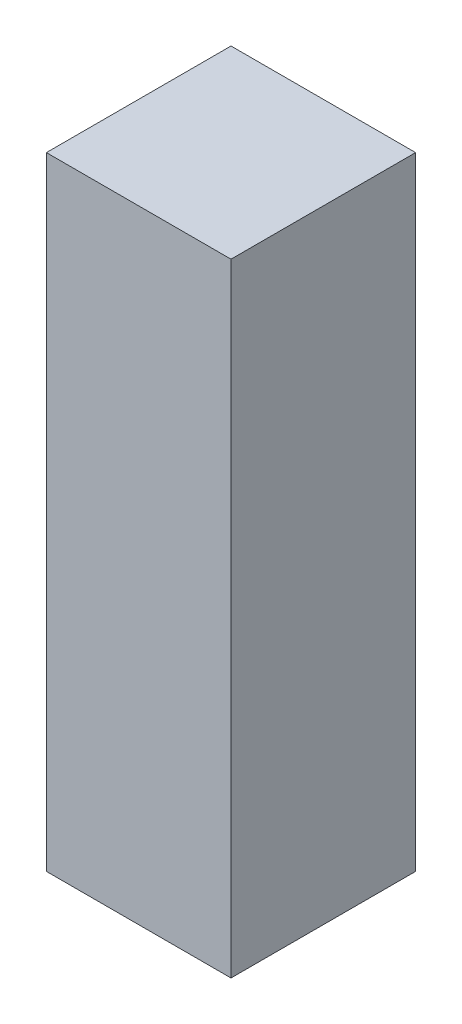
SolidWorks part; units mm, degrees
ref_plane "Plan de face" through (0, 0, 0) normal (0, 0, 1) x (1, 0, 0)
ref_plane "Plan de dessus" through (0, 0, 0) normal (0, 1, 0) x (1, 0, 0)
ref_plane "Plan de droite" through (0, 0, 0) normal (1, 0, 0) x (0, 0, -1)
sketch "Esquisse1" plane through (0, 0, 0) normal (0, 1, 0) x (1, 0, 0)
  line L1 (-15.05, -15.05) -> (15.05, -15.05)
  line L2 (-15.05, -15.05) -> (-15.05, 15.05)
  line L3 (-15.05, 15.05) -> (15.05, 15.05)
  line L4 (15.05, -15.05) -> (15.05, 15.05)
  line L5 (-15.05, -15.05) -> (15.05, 15.05) construction
  line L6 (-15.05, 15.05) -> (15.05, -15.05) construction
  point P0 (0, 0)
  dimension "D1" = 30.1
  dimension "D2" = 30.1
extrude "Boss.-Extru.1" add sketch "Esquisse1" along normal blind 101.5
